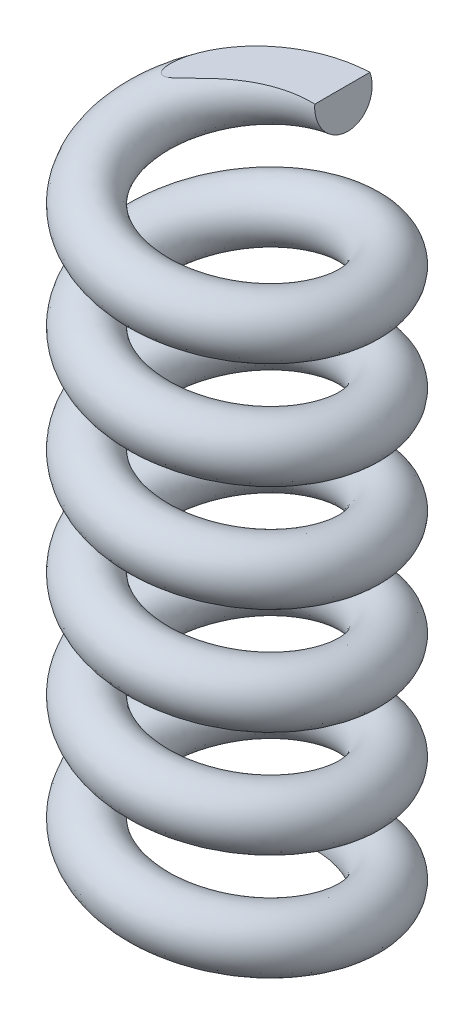
SolidWorks part; units mm, degrees
ref_plane "Front Plane" through (0, 0, 0) normal (0, 0, 1) x (1, 0, 0)
ref_plane "Top Plane" through (0, 0, 0) normal (0, 1, 0) x (1, 0, 0)
ref_plane "Right Plane" through (0, 0, 0) normal (1, 0, 0) x (0, 0, -1)
sketch "Sketch31" plane through (0, 0, 0) normal (0, 1, 0) x (1, 0, 0)
  circle A0 centre (0, 0) radius 15
  dimension "D1" = 30
curve "Helix/Spiral4" pitch 15 height 90 turns 6
sweep "Sweep4" add path "Helix/Spiral4" circular profile diameter 8 parameters "D3"=8
sketch "Sketch38" plane through (0, 0, 0) normal (0, 1, 0) x (1, 0, 0)
  circle A0 centre (0, 0) radius 22.0754
extrude "Cut-Extrude1" cut sketch "Sketch38" against normal blind 10
ref_plane "Plane3" through (0, 90.93, 0) normal (0, 1, 0) x (1, 0, 0)
sketch "Sketch41" plane through (0, 90.93, 0) normal (0, 1, 0) x (1, 0, 0)
  circle A0 centre (0, 0) radius 21.0507
extrude "Cut-Extrude5" cut sketch "Sketch41" along normal blind 10
sketch "Sketch43" plane through (0, 0, 0) normal (0, 0, 1) x (1, 0, 0)
  line L0 (0, 0) -> (-0.148, 90.93)
